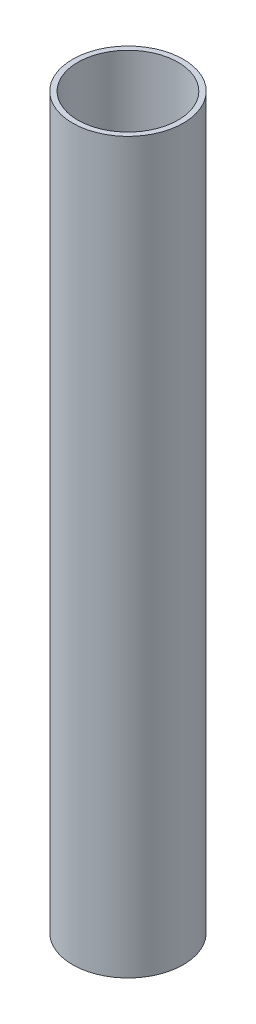
SolidWorks part; units mm, degrees
ref_plane "Front Plane" through (0, 0, 0) normal (0, 0, 1) x (1, 0, 0)
ref_plane "Top Plane" through (0, 0, 0) normal (0, 1, 0) x (1, 0, 0)
ref_plane "Right Plane" through (0, 0, 0) normal (1, 0, 0) x (0, 0, -1)
sketch "Sketch1" plane through (0, 0, 0) normal (0, 1, 0) x (1, 0, 0)
  circle A0 centre (0, 0) radius 27
  circle A1 centre (0, 0) radius 24.46
  dimension "D1" = 54
  dimension "D2" = 2.54
extrude "Boss-Extrude1" add sketch "Sketch1" along normal blind 355.6
